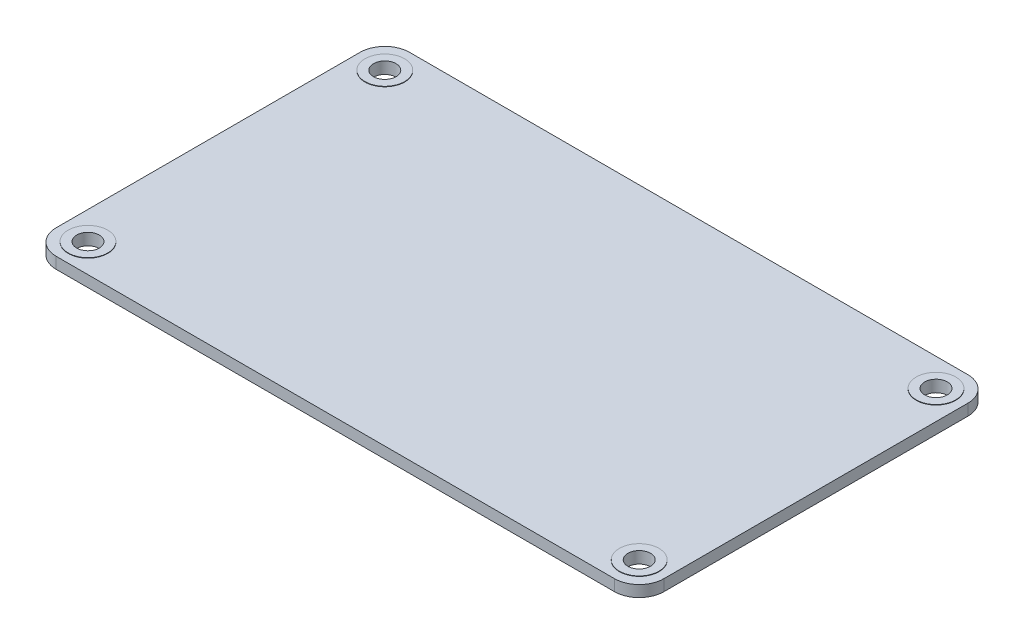
SolidWorks part; units mm, degrees
ref_plane "前视基准面" through (0, 0, 0) normal (0, 0, 1) x (1, 0, 0)
ref_plane "上视基准面" through (0, 0, 0) normal (0, 1, 0) x (1, 0, 0)
ref_plane "右视基准面" through (0, 0, 0) normal (1, 0, 0) x (0, 0, -1)
other "Configuration Table"
sketch "草图1" plane through (0, 0, 0) normal (0, 1, 0) x (1, 0, 0)
  line L1 (-43, -25) -> (43, -25)
  line L2 (-43, -25) -> (-43, 25)
  line L3 (-43, 25) -> (43, 25)
  line L4 (43, -25) -> (43, 25)
  line L5 (-43, -25) -> (43, 25) construction
  line L6 (-43, 25) -> (43, -25) construction
  point P0 (0, 0)
  dimension "D1" = 86
  dimension "D2" = 50
extrude "凸台-拉伸1" add sketch "草图1" along normal blind 1.6
sketch "草图2" plane through (0, 1.6, 0) normal (0, 1, 0) x (1, 0, 0)
  line L0 (-43, 0) -> (43, 0) construction
  line L1 (-43, 25) -> (-43, -25) construction
  line L2 (43, -25) -> (43, 25) construction
  line L3 (43, 0) -> (0, 25) construction
  line L4 (43, 25) -> (-43, 25) construction
  line L5 (0, 25) -> (0, -25) construction
  line L6 (-43, -25) -> (43, -25) construction
  circle A0 centre (-39, 21) radius 1.6
  circle A1 centre (-39, 21) radius 2.8
  circle A2 centre (39, 21) radius 2.8
  circle A3 centre (39, 21) radius 1.6
  circle A4 centre (39, -21) radius 2.8
  circle A5 centre (39, -21) radius 1.6
  circle A6 centre (-39, -21) radius 2.8
  circle A7 centre (-39, -21) radius 1.6
  dimension "D1" = 3.2
  dimension "D2" = 5.6
  dimension "D5" = 21
  dimension "D6" = 39
  dimension "D3" = 2
  dimension "D4" = 2
extrude "凸台-拉伸2" add sketch "草图2" along normal blind 0.06
sketch "草图4" plane through (0, 1.6, 0) normal (0, 1, 0) x (1, 0, 0)
  circle A0 centre (-39, 21) radius 1.6
  circle A1 centre (39, 21) radius 1.6
  circle A2 centre (39, -21) radius 1.6
  circle A3 centre (-39, -21) radius 1.6
  dimension "D1" = 3.2
  dimension "D2" = 3.2
  dimension "D3" = 3.2
  dimension "D4" = 3.2
extrude "切除-拉伸1" cut sketch "草图4" against normal through all
fillet "圆角1" radius 3.5 4 edges at (-43, 0.8, -25) (43, 0.8, -25) (43, 0.8, 25) (-43, 0.8, 25)
